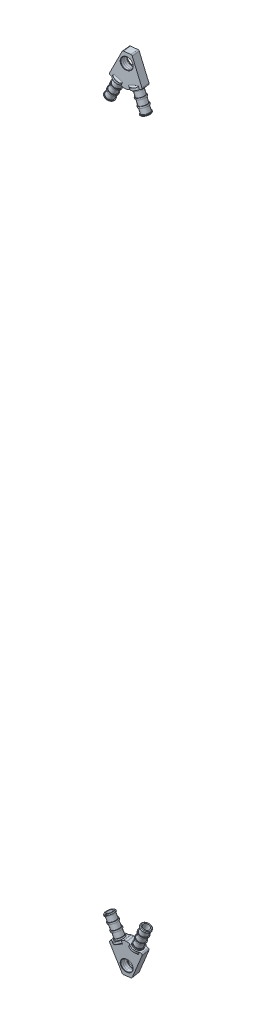
SolidWorks part; units mm, degrees
ref_plane "Front Plane" through (0, 0, 0) normal (0, 0, 1) x (1, 0, 0)
ref_plane "Top Plane" through (0, 0, 0) normal (0, 1, 0) x (1, 0, 0)
ref_plane "Right Plane" through (0, 0, 0) normal (1, 0, 0) x (0, 0, -1)
sketch3d "3DSketch1"
  line L0 (1150, 574, 138) -> (1280, 250, 132)
  line L1 (1280, 250, 132) -> (1020, 290, 165)
  line L2 (1020, 290, 165) -> (1150, 574, 138)
  point P0 (1020, 290, 165)
  point P1 (1280, 250, 132)
  point P2 (1150, 574, 138)
  point P3 (1150, 574, 138)
ref_plane "Plane1" through (40.2285, 10.5074, 304.2154) normal (0.131, 0.0342, 0.9908) x (0.9914, -0.0045, -0.1309)
sketch "Sketch1" plane through (40.2285, 10.5074, 304.2154) normal (0.131, 0.0342, 0.9908) x (0.9914, -0.0045, -0.1309)
  line L0 (1113.5581, 582.4609) -> (1125.7924, 582.4609)
  line L1 (1125.7924, 582.4609) -> (1140.8827, 545.2215)
  line L2 (1140.8827, 545.2215) -> (1120.4931, 536.9592)
  line L4 (1116.8644, 537.0437) -> (1096.8813, 546.2457)
  line L5 (1096.8813, 546.2457) -> (1113.5581, 582.4609)
  line L6 (988.2907, 284.1316) -> (1119.4211, 568.8943) construction
  line L7 (1119.4211, 568.8943) -> (1250.5514, 245.2945) construction
  line L8 (1106.8729, 541.6447) -> (1119.4211, 568.8943)
  line L9 (1119.4211, 568.8943) -> (1130.6879, 541.0904)
  line L10 (1116.8644, 537.0437) -> (1120.4931, 536.9592)
  circle A0 centre (1119.4211, 568.8943) radius 8
  point P15 (1130.6879, 541.0904)
  point P16 (1106.8729, 541.6447)
  dimension "D1" = 22
  dimension "D4" = 16
  dimension "D2" = 22
  dimension "D3" = 30
extrude "Boss-Extrude1" add sketch "Sketch1" along normal mid plane 12 contours A0 L9 L2 L1 L0 L5 L4 L8 | A0 L8 L4 L10 L2 L9
fillet "Fillet1" radius 2 6 edges at (1171.2766, 550.2443, 136.007) (1151.0628, 542.0791, 138.962) (1147.4654, 542.1799, 139.4342) (1127.6546, 551.4668, 141.7332) (1156.3164, 587.5297, 136.6974) (1144.1876, 587.5851, 138.2994)
ref_plane "Plane2" through (395.9916, 865.0893, -82.2444) normal (-0.4147, -0.9059, 0.0861) x (-0.91, 0.4128, -0.0392)
sketch "Sketch2" plane through (395.9916, 865.0893, -82.2444) normal (-0.4147, -0.9059, 0.0861) x (-0.91, 0.4128, -0.0392)
  circle A0 centre (-814.9344, -191.706) radius 9
extrude "Boss-Extrude2" add sketch "Sketch2" against normal blind 3
sketch "Sketch4" plane through (395.9916, 865.0893, -82.2444) normal (-0.4147, -0.9059, 0.0861) x (-0.91, 0.4128, -0.0392)
  circle A0 centre (-814.9344, -191.706) radius 6
  dimension "D1" = 12
extrude "Boss-Extrude4" add sketch "Sketch4" along normal blind 31
sketch "Sketch7" plane through (395.9916, 865.0893, -82.2444) normal (-0.4147, -0.9059, 0.0861) x (-0.91, 0.4128, -0.0392)
  circle A0 centre (-814.9344, -191.706) radius 7
  circle A1 centre (-814.9344, -191.706) radius 6
  dimension "D1" = 14
  dimension "D2" = 12
extrude "Boss-Extrude5" add sketch "Sketch7" along normal blind 2
pattern_linear "LPattern1" count 4 spacing 9.6667 along (-0.4147, -0.9059, 0.0861) of "Boss-Extrude5"
chamfer "Chamfer1" distance 1 angle 45 1 edges at (1131.0702, 515.8273, 143.2535)
ref_plane "Plane5" through (383.1369, 837.0068, -79.5746) normal (-0.4147, -0.9059, 0.0861) x (-0.91, 0.4128, -0.0392)
sketch "Sketch8" plane through (383.1369, 837.0068, -79.5746) normal (-0.4147, -0.9059, 0.0861) x (-0.91, 0.4128, -0.0392)
  circle A0 centre (-814.9344, -191.706) radius 4.5
ref_plane "Plane6" through (701.3399, -328.7734, -81.3873) normal (-0.9005, 0.4221, 0.1045) x (0.0946, -0.0444, 0.9945)
sketch "Sketch9" plane through (701.3399, -328.7734, -81.3873) normal (-0.9005, 0.4221, 0.1045) x (0.0946, -0.0444, 0.9945)
  line L0 (225.8775, 947.0805) -> (230.3606, 947.4702)
  line L1 (221.3944, 946.6908) -> (230.3606, 947.4702) construction
  line L2 (230.3606, 947.4702) -> (228.5132, 968.7234)
  line L3 (230.0075, 968.8533) -> (218.0526, 967.8141) construction
  line L4 (220.5951, 1007.8513) -> (241.2991, 769.6651) construction
  line L6 (223.6404, 972.8168) -> (225.8775, 947.0805)
  arc A0 (228.5132, 968.7234) -> (223.6404, 972.8168) centre (224.0301, 968.3337) ccw
  dimension "D1" = 4.5
revolve "Cut-Revolve1" cut sketch "Sketch9" angle 360 about L6
ref_plane "Plane8" through (-28.6092, 71.3028, 1.3204) normal (0.3723, -0.9279, -0.0172) x (-0.9281, -0.3723, -0.0069)
sketch "Sketch10" plane through (-28.6092, 71.3028, 1.3204) normal (0.3723, -0.9279, -0.0172) x (-0.9281, -0.3723, -0.0069)
  circle A0 centre (-1281.9468, -127.3485) radius 9
  dimension "D1" = 18
extrude "Boss-Extrude6" add sketch "Sketch10" against normal blind 3
sketch "Sketch11" plane through (-28.6092, 71.3028, 1.3204) normal (0.3723, -0.9279, -0.0172) x (-0.9281, -0.3723, -0.0069)
  circle A0 centre (-1281.9468, -127.3485) radius 6
  dimension "D1" = 12
extrude "Boss-Extrude7" add sketch "Sketch11" along normal blind 31
sketch "Sketch12" plane through (-28.6092, 71.3028, 1.3204) normal (0.3723, -0.9279, -0.0172) x (-0.9281, -0.3723, -0.0069)
  circle A0 centre (-1281.9468, -127.3485) radius 6
  circle A1 centre (-1281.9468, -127.3485) radius 7
  dimension "D1" = 12
  dimension "D2" = 14
extrude "Boss-Extrude8" add sketch "Sketch12" along normal blind 2
pattern_linear "LPattern2" count 4 spacing 9.6667 along (0.3723, -0.9279, -0.0172) of "Boss-Extrude8"
chamfer "Chamfer2" distance 1 angle 45 1 edges at (1179.2083, 520.0021, 136.9518)
ref_plane "Plane9" through (1149.5504, 464.3514, -168.0514) normal (0.9188, 0.3711, -0.1343) x (0.3723, -0.9279, -0.0172)
sketch "Sketch13" plane through (1149.5504, 464.3514, -168.0514) normal (0.9188, 0.3711, -0.1343) x (0.3723, -0.9279, -0.0172)
  line L0 (-45.8396, -307.0436) -> (-45.8396, -302.5436)
  line L1 (-45.8396, -313.0436) -> (-45.8396, -301.0436) construction
  line L2 (-45.8396, -302.5436) -> (-67.1729, -302.5436)
  line L3 (-67.1729, -301.0436) -> (-67.1729, -313.0436) construction
  line L4 (-106.8396, -307.0436) -> (242.3194, -307.0436) construction
  line L5 (-71.6729, -307.0436) -> (-45.8396, -307.0436)
  arc A0 (-67.1729, -302.5436) -> (-71.6729, -307.0436) centre (-67.1729, -307.0436) ccw
  dimension "D1" = 4.5
revolve "Cut-Revolve2" cut sketch "Sketch13" angle 360 about L5
fillet "Fillet2" radius 2 4 edges at (1159.2666, 548.7402, 131.5913) (1138.0179, 549.3357, 134.3806) (1160.8388, 549.1508, 143.4808) (1139.5901, 549.7463, 146.2701)
chamfer "Chamfer3" distance 0.5 angle 45 2 edges at (1158.7171, 574.2053, 142.896) (1157.1448, 573.7947, 131.0065)
ref_plane "Plane10" through (0, 0, 138) normal (0, 0, 1) x (1, 0, 0)
sketch "Sketch14" plane through (0, 0, 138) normal (0, 0, 1) x (1, 0, 0)
  circle A0 centre (1150, 574) radius 8
  dimension "D1" = 16
extrude "Cut-Extrude1" cut sketch "Sketch14" along normal blind 3 and the other way blind 2
sketch "Sketch15" plane through (0, 0, 138) normal (0, 0, 1) x (1, 0, 0)
  circle A0 centre (1150, 574) radius 8.75
  dimension "D1" = 17.5
extrude "Cut-Extrude2" cut sketch "Sketch15" against normal blind 1.05 from offset 2.5 offset against normal yes
mirror "镜向1" about plane through (0, 0, 0) normal (0, 1, 0) of bodies 115
